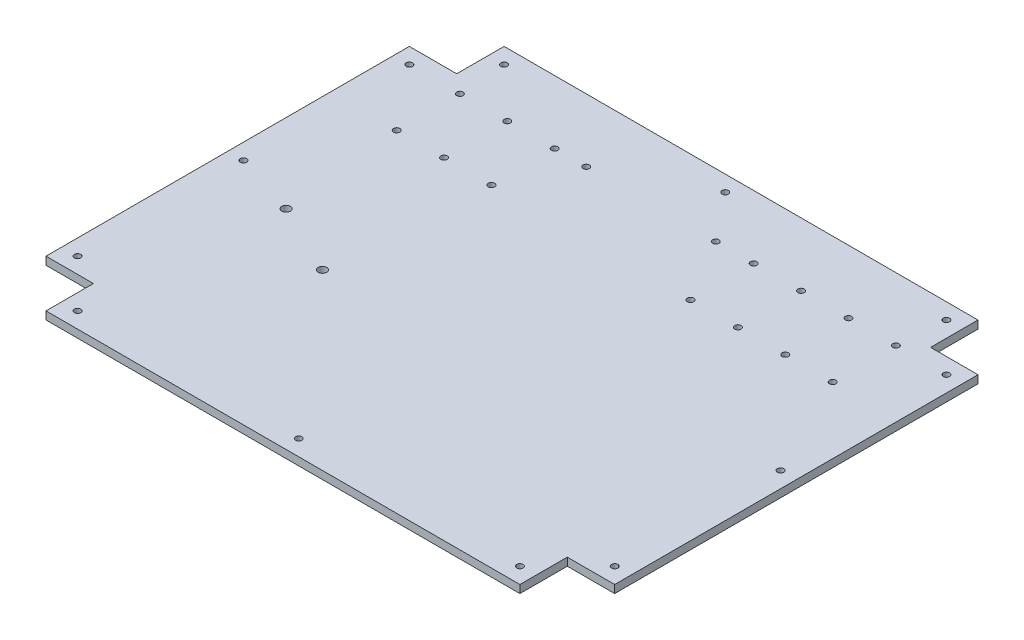
SolidWorks part; units mm, degrees
ref_plane "Front Plane" through (0, 0, 0) normal (0, 0, 1) x (1, 0, 0)
ref_plane "Top Plane" through (0, 0, 0) normal (0, 1, 0) x (1, 0, 0)
ref_plane "Right Plane" through (0, 0, 0) normal (1, 0, 0) x (0, 0, -1)
sketch "Sketch1" plane through (0, 0, 0) normal (0, 1, 0) x (1, 0, 0)
  line L0 (228.6, 368.3) -> (228.6, 0) construction
  line L1 (0, 0) -> (457.2, 0)
  line L2 (0, 0) -> (0, 368.3)
  line L3 (0, 368.3) -> (457.2, 368.3)
  line L4 (457.2, 0) -> (457.2, 368.3)
  line L6 (444.5, 12.7) -> (12.7, 12.7) construction
  line L7 (444.5, 12.7) -> (444.5, 355.6) construction
  line L8 (444.5, 355.6) -> (12.7, 355.6) construction
  line L9 (12.7, 12.7) -> (12.7, 355.6) construction
  line L10 (444.5, 12.7) -> (12.7, 355.6) construction
  line L11 (444.5, 355.6) -> (12.7, 12.7) construction
  circle A0 centre (50.8, 355.6) radius 2.5527
  circle A1 centre (406.4, 355.6) radius 2.5527
  circle A2 centre (406.4, 12.7) radius 2.5527
  circle A3 centre (50.8, 12.7) radius 2.5527
  circle A4 centre (228.6, 12.7) radius 2.5527
  circle A5 centre (228.6, 355.6) radius 2.5527
  circle A6 centre (12.7, 184.15) radius 2.5527
  circle A7 centre (444.5, 184.15) radius 2.5527
  circle A8 centre (12.7, 50.8) radius 2.5527
  circle A9 centre (444.5, 50.8) radius 2.5527
  circle A10 centre (444.5, 317.5) radius 2.5527
  circle A11 centre (12.7, 317.5) radius 2.5527
  point P7 (228.6, 184.15)
  dimension "D5" = 5.1054
  dimension "D6" = 5.1054
  dimension "D7" = 50.8
  dimension "D8" = 5.1054
  dimension "D9" = 5.1054
  dimension "D10" = 50.8
  dimension "D11" = 5.1054
  dimension "D12" = 5.1054
  dimension "D13" = 5.1054
  dimension "D15" = 5.1054
  dimension "D18" = 5.1054
  dimension "D19" = 5.1054
  dimension "D21" = 5.1054
  dimension "D23" = 5.1054
  dimension "D1" = 457.2
  dimension "D2" = 368.3
  dimension "D3" = 12.7
  dimension "D4" = 12.7
  dimension "D14" = 50.8
  dimension "D16" = 50.8
  dimension "D17" = 50.8
  dimension "D20" = 50.8
  dimension "D22" = 50.8
  dimension "D24" = 50.8
extrude "Boss-Extrude1" add sketch "Sketch1" along normal blind 6.35
sketch "Sketch2" plane through (0, 6.35, 0) normal (0, 1, 0) x (1, 0, 0)
  line L0 (0, 368.3) -> (0, 0) construction
  line L1 (457.2, 368.3) -> (0, 368.3) construction
  line L2 (457.2, 0) -> (457.2, 368.3) construction
  line L3 (0, 0) -> (457.2, 0) construction
  line L4 (0, 368.3) -> (0, 0)
  line L5 (457.2, 368.3) -> (0, 368.3)
  line L6 (457.2, 0) -> (457.2, 368.3)
  line L7 (0, 0) -> (457.2, 0)
  line L9 (0, 368.3) -> (38.1, 368.3)
  line L10 (0, 368.3) -> (0, 330.2)
  line L11 (0, 330.2) -> (38.1, 330.2)
  line L12 (38.1, 368.3) -> (38.1, 330.2)
  line L13 (0, 0) -> (38.1, 0)
  line L14 (0, 0) -> (0, 38.1)
  line L15 (0, 38.1) -> (38.1, 38.1)
  line L16 (38.1, 0) -> (38.1, 38.1)
  line L17 (457.2, 0) -> (419.1, 0)
  line L18 (457.2, 0) -> (457.2, 38.1)
  line L19 (457.2, 38.1) -> (419.1, 38.1)
  line L20 (419.1, 0) -> (419.1, 38.1)
  line L21 (457.2, 368.3) -> (419.1, 368.3)
  line L22 (457.2, 368.3) -> (457.2, 330.2)
  line L23 (457.2, 330.2) -> (419.1, 330.2)
  line L24 (419.1, 368.3) -> (419.1, 330.2)
  line M9 (0, 368.3) -> (0, 0)
  line M10 (0, 0) -> (457.2, 0)
  line M11 (457.2, 0) -> (457.2, 368.3)
  line M12 (457.2, 368.3) -> (0, 368.3)
  dimension "D1" = 38.1
  dimension "D2" = 38.1
  dimension "D3" = 38.1
  dimension "D4" = 38.1
  dimension "D5" = 38.1
  dimension "D6" = 38.1
  dimension "D7" = 38.1
  dimension "D8" = 38.1
extrude "Cut-Extrude1" cut sketch "Sketch2" against normal up to next contours L16 L15 M10 M9 | L12 L5 L11 M9 | L24 L23 M12 M11 | L20 L19 M10 M11
sketch "Sketch3" plane through (0, 6.35, 0) normal (0, 1, 0) x (1, 0, 0)
  line L0 (12.7, 317.5) -> (444.5, 317.5) construction
  line L1 (12.7, 266.7) -> (444.5, 266.7) construction
  line L2 (38.1, 317.5) -> (38.1, 266.7) construction
  line L3 (53.34, 266.7) -> (53.34, 317.5) construction
  line L4 (91.44, 266.7) -> (91.44, 317.5) construction
  line L5 (129.54, 266.7) -> (129.54, 317.5) construction
  line L6 (289.56, 266.7) -> (289.56, 317.5) construction
  line L7 (419.1, 317.5) -> (419.1, 266.7) construction
  line L8 (419.1, 266.7) -> (403.86, 266.7) construction
  line L9 (403.86, 266.7) -> (403.86, 317.5) construction
  line L10 (365.76, 266.7) -> (365.76, 317.5) construction
  line L11 (327.66, 266.7) -> (327.66, 317.5) construction
  line L12 (419.1, 368.3) -> (419.1, 330.2) construction
  line L13 (38.1, 368.3) -> (38.1, 330.2) construction
  circle A0 centre (53.34, 266.7) radius 2.5527
  circle A1 centre (53.34, 317.5) radius 2.5527
  circle A2 centre (91.44, 266.7) radius 2.5527
  circle A3 centre (91.44, 317.5) radius 2.5527
  circle A4 centre (129.54, 266.7) radius 2.5527
  circle A5 centre (129.54, 317.5) radius 2.5527
  circle A6 centre (289.56, 266.7) radius 2.5527
  circle A7 centre (289.56, 317.5) radius 2.5527
  circle A8 centre (403.86, 266.7) radius 2.5527
  circle A9 centre (403.86, 317.5) radius 2.5527
  circle A10 centre (365.76, 266.7) radius 2.5527
  circle A11 centre (365.76, 317.5) radius 2.5527
  circle A12 centre (327.66, 266.7) radius 2.5527
  circle A13 centre (327.66, 317.5) radius 2.5527
  circle A14 centre (259.08, 317.5) radius 2.5527
  circle A15 centre (154.94, 317.5) radius 2.5527
  dimension "D3" = 5.1054
  dimension "D4" = 5.1054
  dimension "D7" = 5.1054
  dimension "D8" = 5.1054
  dimension "D10" = 5.1054
  dimension "D11" = 5.1054
  dimension "D1" = 50.8
  dimension "D2" = 15.24
  dimension "D6" = 15.24
  dimension "D12" = 104.14
  dimension "D13" = 38.1
  dimension "D14" = 38.1
  dimension "D15" = 25.4
  dimension "D5" = 3
  dimension "D9" = 4
extrude "Cut-Extrude2" cut sketch "Sketch3" against normal up to next
sketch "Sketch5" plane through (0, 0, 0) normal (0, -1, 0) x (1, 0, 0)
  line L0 (0, -38.1) -> (38.1, -38.1) construction
  line L1 (0, -330.2) -> (0, -38.1) construction
  line L4 (63.5, -167.64) -> (120.65, -167.64) construction
  line L5 (63.5, -167.64) -> (63.5, -139.7) construction
  line L6 (63.5, -139.7) -> (120.65, -139.7) construction
  line L7 (120.65, -167.64) -> (120.65, -139.7) construction
  circle A2 centre (63.5, -167.64) radius 3.429
  circle A3 centre (120.65, -139.7) radius 3.429
  dimension "D3" = 101.6
  dimension "D1" = 57.15
  dimension "D2" = 27.94
  dimension "D5" = 63.5
extrude "Cut-Extrude3" cut sketch "Sketch5" against normal up to next
